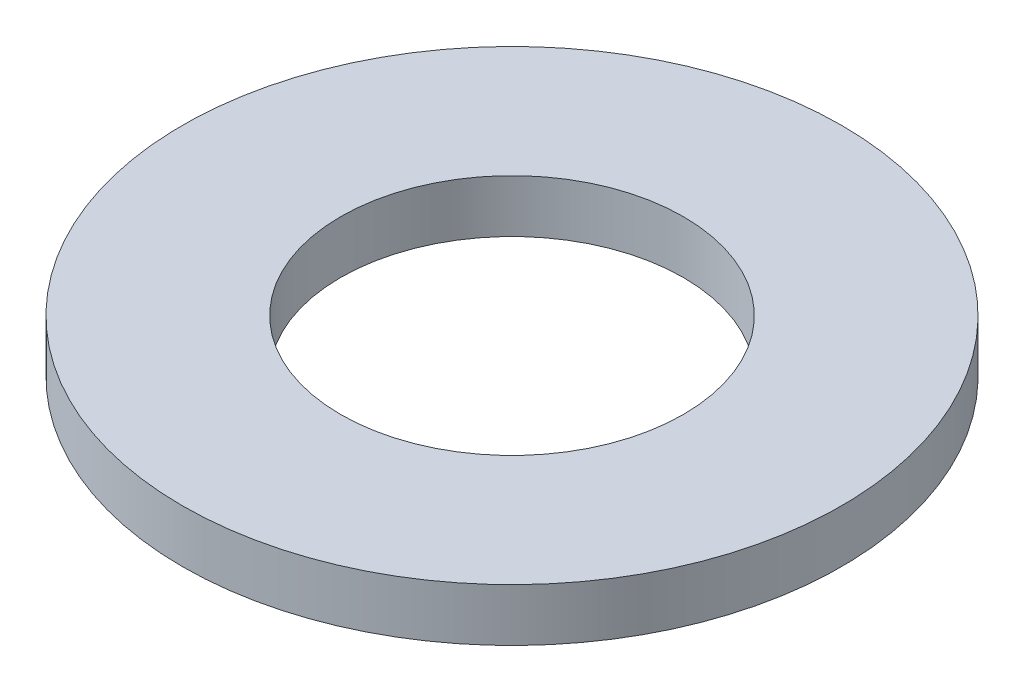
SolidWorks part; units mm, degrees
material "Nylon 6/10"
ref_plane "Front Plane" through (0, 0, 0) normal (0, 0, 1) x (1, 0, 0)
ref_plane "Top Plane" through (0, 0, 0) normal (0, 1, 0) x (1, 0, 0)
ref_plane "Right Plane" through (0, 0, 0) normal (1, 0, 0) x (0, 0, -1)
sketch "Sketch1" plane through (0, 0, 0) normal (0, 1, 0) x (1, 0, 0)
  circle A0 centre (0, 0) radius 4.953
  circle A1 centre (0, 0) radius 9.525
  dimension "D1" = 9.906
  dimension "D2" = 19.05
extrude "Boss-Extrude1" add sketch "Sketch1" along normal blind 1.524
